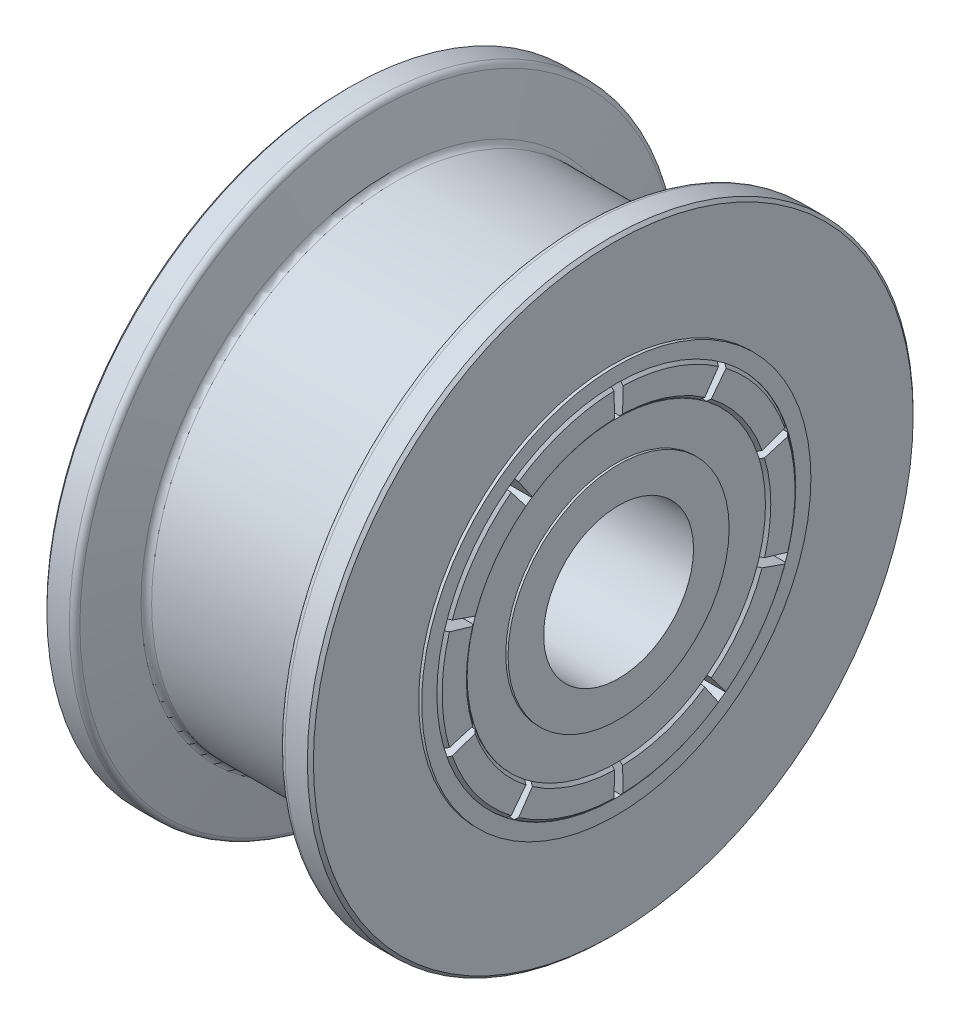
SolidWorks part; units mm, degrees
ref_plane "Front Plane" through (0, 0, 0) normal (0, 0, 1) x (1, 0, 0)
ref_plane "Top Plane" through (0, 0, 0) normal (0, 1, 0) x (1, 0, 0)
ref_plane "Right Plane" through (0, 0, 0) normal (1, 0, 0) x (0, 0, -1)
sketch "Sketch1" plane through (0, 0, 0) normal (1, 0, 0) x (0, 0, -1)
  circle A0 centre (0, 0) radius 10
  circle A1 centre (0, 0) radius 6.425
  dimension "D1" = 20
  dimension "D2" = 12.85
extrude "Boss-Extrude1" add sketch "Sketch1" along normal mid plane 8.8
sketch "Sketch2" plane through (0, 0, 0) normal (0, 0, 1) x (1, 0, 0)
  line L0 (0, 10.5149) -> (0, 0) construction
  line L1 (-5.5837, 0) -> (5.1822, 0) construction
  line L2 (-3.4, 10) -> (-2.95, 8.05)
  line L3 (4.4, 10) -> (-4.4, 10) construction
  line L4 (-2.95, 8.05) -> (2.95, 8.05)
  line L5 (-3.4, 10) -> (3.4, 10)
  line L6 (3.4, 10) -> (2.95, 8.05)
  point P12 (0, 8.05)
  point P13 (0, 10)
  dimension "D1" = 3.4
  dimension "D2" = 2.95
  dimension "D3" = 8.05
revolve "Cut-Revolve1" cut sketch "Sketch2" angle 360 about L1
fillet "Fillet1" radius 0.2 4 edges at (-3.4, 0, 10) (3.4, 0, 10) (-2.95, 0, 8.05) (2.95, 0, 8.05)
chamfer "Chamfer1" distance 0.1 angle 45 2 edges at (4.4, 0, -10) (-4.4, 0, -10)
sketch "Sketch3" plane through (0, 0, 0) normal (1, 0, 0) x (0, 0, -1)
  circle A0 centre (0, 0) radius 2.475
  circle A1 centre (0, 0) radius 3.65
  dimension "D1" = 4.95
  dimension "D2" = 7.3
extrude "Boss-Extrude2" add sketch "Sketch3" along normal mid plane 9.15 separate body
sketch "Sketch4" plane through (0, 0, 0) normal (1, 0, 0) x (0, 0, -1)
  circle A0 centre (0, 0) radius 3.65 construction
  circle A1 centre (0, 0) radius 3.65
  circle A2 centre (0, 0) radius 4.925
  dimension "D1" = 9.85
extrude "Boss-Extrude3" add sketch "Sketch4" along normal mid plane 9 separate body
sketch "Sketch5" plane through (0, 0, 0) normal (1, 0, 0) x (0, 0, -1)
  circle A0 centre (0, 0) radius 4.925 construction
  circle A1 centre (0, 0) radius 4.925
  circle A2 centre (0, 0) radius 5.925
  dimension "D1" = 1
extrude "Boss-Extrude4" add sketch "Sketch5" along normal mid plane 9.15 separate body
chamfer "Chamfer3" distance 0.1 angle 45 4 edges at (4.575, 0, -5.925) (4.575, 0, -4.925) (-4.575, 0, -5.925) (-4.575, 0, -4.925)
sketch "Sketch6" plane through (0, 0, 0) normal (1, 0, 0) x (0, 0, -1)
  line L0 (0, 0) -> (0, 10.4898) construction
  line L1 (0.1289, 4.9233) -> (0.1551, 5.923)
  line L2 (-0.1289, 4.9233) -> (-0.1551, 5.923)
  line L3 (2.9982, 3.9073) -> (3.6069, 4.7006)
  line L4 (2.7896, 4.0588) -> (3.356, 4.8829)
  line L5 (4.7222, 1.3988) -> (5.681, 1.6828)
  line L6 (4.6425, 1.644) -> (5.5852, 1.9778)
  line L7 (4.6425, -1.644) -> (5.5852, -1.9778)
  line L8 (4.7222, -1.3988) -> (5.681, -1.6828)
  line L9 (2.7896, -4.0588) -> (3.356, -4.8829)
  line L10 (2.9982, -3.9073) -> (3.6069, -4.7006)
  line L11 (-0.1289, -4.9233) -> (-0.1551, -5.923)
  line L12 (0.1289, -4.9233) -> (0.1551, -5.923)
  line L13 (-2.9982, -3.9073) -> (-3.6069, -4.7006)
  line L14 (-2.7896, -4.0588) -> (-3.356, -4.8829)
  line L15 (-4.7222, -1.3988) -> (-5.681, -1.6828)
  line L16 (-4.6425, -1.644) -> (-5.5852, -1.9778)
  line L17 (-4.6425, 1.644) -> (-5.5852, 1.9778)
  line L18 (-4.7222, 1.3988) -> (-5.681, 1.6828)
  line L19 (-2.7896, 4.0588) -> (-3.356, 4.8829)
  line L20 (-2.9982, 3.9073) -> (-3.6069, 4.7006)
  arc A0 (3.6069, 4.7006) -> (3.356, 4.8829) centre (0, 0) ccw
  circle A1 centre (0, 0) radius 5.925 construction
  circle A2 centre (0, 0) radius 4.925 construction
  arc A3 (0.1551, 5.923) -> (-0.1551, 5.923) centre (0, 0) ccw
  arc A4 (0.1289, 4.9233) -> (-0.1289, 4.9233) centre (0, 0) ccw
  arc A5 (2.9982, 3.9073) -> (2.7896, 4.0588) centre (0, 0) ccw
  arc A6 (5.681, 1.6828) -> (5.5852, 1.9778) centre (0, 0) ccw
  arc A7 (4.7222, 1.3988) -> (4.6425, 1.644) centre (0, 0) ccw
  arc A8 (5.5852, -1.9778) -> (5.681, -1.6828) centre (0, 0) ccw
  arc A9 (4.6425, -1.644) -> (4.7222, -1.3988) centre (0, 0) ccw
  arc A10 (3.356, -4.8829) -> (3.6069, -4.7006) centre (0, 0) ccw
  arc A11 (2.7896, -4.0588) -> (2.9982, -3.9073) centre (0, 0) ccw
  arc A12 (-0.1551, -5.923) -> (0.1551, -5.923) centre (0, 0) ccw
  arc A13 (-0.1289, -4.9233) -> (0.1289, -4.9233) centre (0, 0) ccw
  arc A14 (-3.6069, -4.7006) -> (-3.356, -4.8829) centre (0, 0) ccw
  arc A15 (-2.9982, -3.9073) -> (-2.7896, -4.0588) centre (0, 0) ccw
  arc A16 (-5.681, -1.6828) -> (-5.5852, -1.9778) centre (0, 0) ccw
  arc A17 (-4.7222, -1.3988) -> (-4.6425, -1.644) centre (0, 0) ccw
  arc A18 (-5.5852, 1.9778) -> (-5.681, 1.6828) centre (0, 0) ccw
  arc A19 (-4.6425, 1.644) -> (-4.7222, 1.3988) centre (0, 0) ccw
  arc A20 (-3.356, 4.8829) -> (-3.6069, 4.7006) centre (0, 0) ccw
  arc A21 (-2.7896, 4.0588) -> (-2.9982, 3.9073) centre (0, 0) ccw
  point P47 (0, 0)
  dimension "D1" = 1.5
  dimension "D2" = 1.5
  dimension "D3" = 10
extrude "Cut-Extrude1" cut sketch "Sketch6" against normal through all both and the other way through all
sketch "Sketch7" plane through (0, 0, 0) normal (1, 0, 0) x (0, 0, -1)
  circle A0 centre (0, 0) radius 5.925
  circle A1 centre (0, 0) radius 6.425 construction
  circle A2 centre (0, 0) radius 6.425
extrude "Boss-Extrude5" add sketch "Sketch7" along normal mid plane 9 separate body
